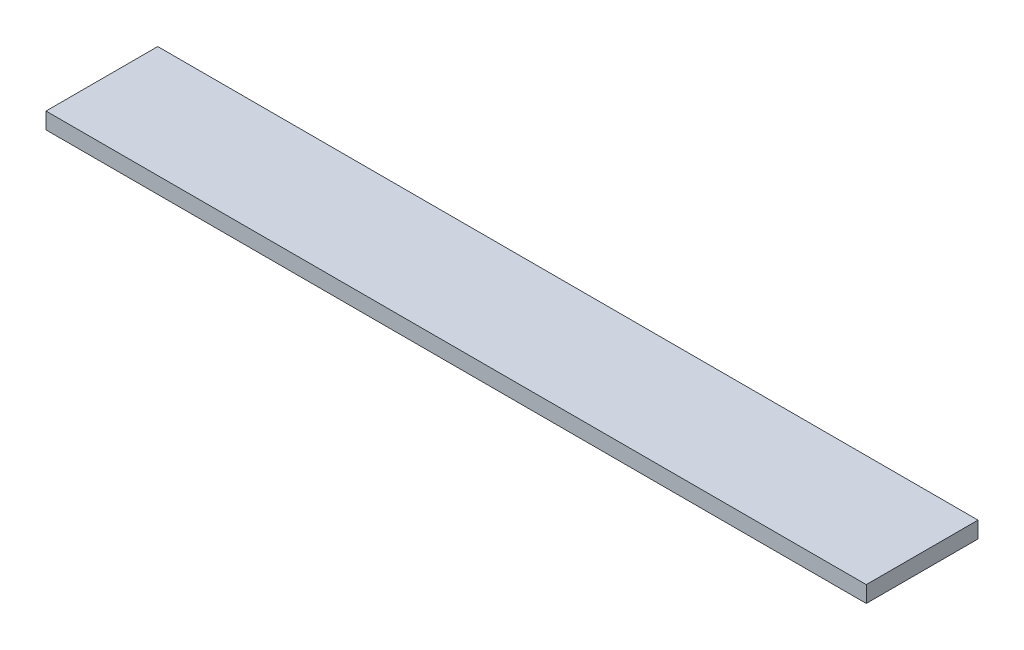
SolidWorks part; units mm, degrees
ref_plane "Front Plane" through (0, 0, 0) normal (0, 0, 1) x (1, 0, 0)
ref_plane "Top Plane" through (0, 0, 0) normal (0, 1, 0) x (1, 0, 0)
ref_plane "Right Plane" through (0, 0, 0) normal (1, 0, 0) x (0, 0, -1)
sketch "Sketch1" plane through (0, 0, 0) normal (0, 1, 0) x (1, 0, 0)
  line L1 (0, 0) -> (60.2, 0)
  line L2 (0, 0) -> (0, -8.2)
  line L3 (0, -8.2) -> (60.2, -8.2)
  line L4 (60.2, 0) -> (60.2, -8.2)
  dimension "D1" = 8.2
  dimension "D2" = 60.2
extrude "Boss-Extrude1" add sketch "Sketch1" along normal blind 1.2
sketch "Sketch2" plane through (0, 0, 0) normal (0, -1, 0) x (-1, 0, 0)
  circle A0 centre (-7.52, -1.88) radius 1.5
  circle A1 centre (-57.8, -1.88) radius 1.5
  circle A2 centre (-57.8, -6.12) radius 1.5
  dimension "D1" = 3
  dimension "D2" = 3
  dimension "D3" = 3
extrude "Cut-Extrude1" cut sketch "Sketch2" against normal blind 0.5
